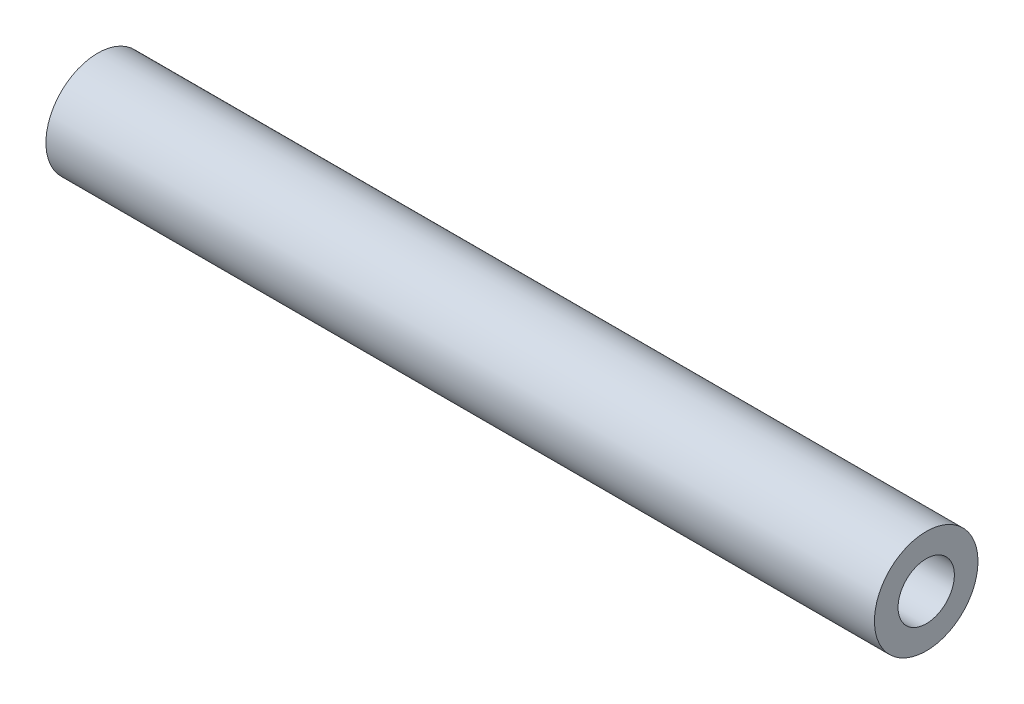
SolidWorks part; units mm, degrees
ref_plane "Front Plane" through (0, 0, 0) normal (0, 0, 1) x (1, 0, 0)
ref_plane "Top Plane" through (0, 0, 0) normal (0, 1, 0) x (1, 0, 0)
ref_plane "Right Plane" through (0, 0, 0) normal (1, 0, 0) x (0, 0, -1)
sketch "Sketch1" plane through (0, 0, 0) normal (1, 0, 0) x (0, 0, -1)
  circle A0 centre (0, 0) radius 3.175
  dimension "D1" = 6.35
extrude "Boss-Extrude1" add sketch "Sketch1" along normal blind 50.8
hole_wizard "#8-32 Tapped Hole1" positions "Sketch2" profile "Sketch4" tap size "#8-32" standard "ANSI Inch"
sketch "Sketch2" plane through (50.8, 0, 0) normal (1, 0, 0) x (0, 0, -1)
  point P0 (0, 0)
sketch "Sketch4" plane through (50.8, 0, 0) normal (0, 1, 0) x (0, 0, -1)
  line L0 (0, 0) -> (0, 26.4378)
  line L1 (0, 26.4378) -> (1.7272, 25.4)
  line L2 (1.7272, 25.4) -> (1.7272, 0)
  line L5 (1.7272, 0) -> (0, 0)
  line L10 (0, 26.4378) -> (-1.7272, 25.4) construction
  line L11 (0, -6.35) -> (0, 107.95) construction
  dimension "Tap Drill Dia." = 3.4544
  dimension "Tap Drill Depth" = 25.4
  dimension "Drill Angle" = 118
cosmetic thread "Hole Thread1"
